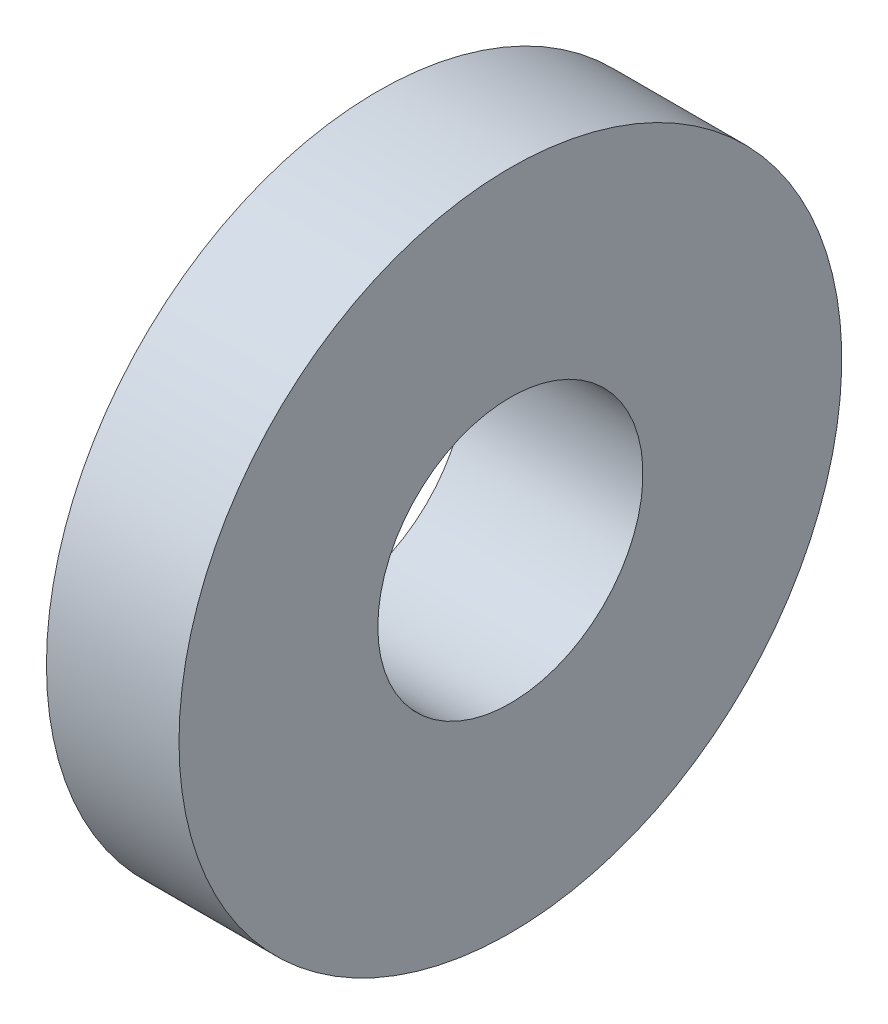
SolidWorks part; units mm, degrees
ref_plane "Front Plane" through (0, 0, 0) normal (0, 0, 1) x (1, 0, 0)
ref_plane "Top Plane" through (0, 0, 0) normal (0, 1, 0) x (1, 0, 0)
ref_plane "Right Plane" through (0, 0, 0) normal (1, 0, 0) x (0, 0, -1)
sketch "Sketch1" plane through (0, 0, 0) normal (0, 0, 1) x (1, 0, 0)
  line L0 (0, 0) -> (2, 0) construction
  line L1 (0, 0) -> (0, 2.5)
  line L2 (0, 2.5) -> (0.5, 2.5)
  line L3 (0.5, 2.5) -> (0.5, 3.75)
  line L4 (0.5, 3.75) -> (2, 3.75)
  line L5 (2, 3.75) -> (2, 0)
  line L6 (0, 0) -> (2, 0)
  dimension "D1" = 2
  dimension "D2" = 1.5
  dimension "D3" = 2.5
  dimension "D4" = 3.75
revolve "Revolve1" add sketch "Sketch1" angle 360 about L0
sketch "Sketch2" plane through (0, 0, 0) normal (-1, 0, 0) x (0, 0, 1)
  circle A0 centre (0, 0) radius 1.5
extrude "Cut-Extrude1" cut sketch "Sketch2" against normal blind 10
